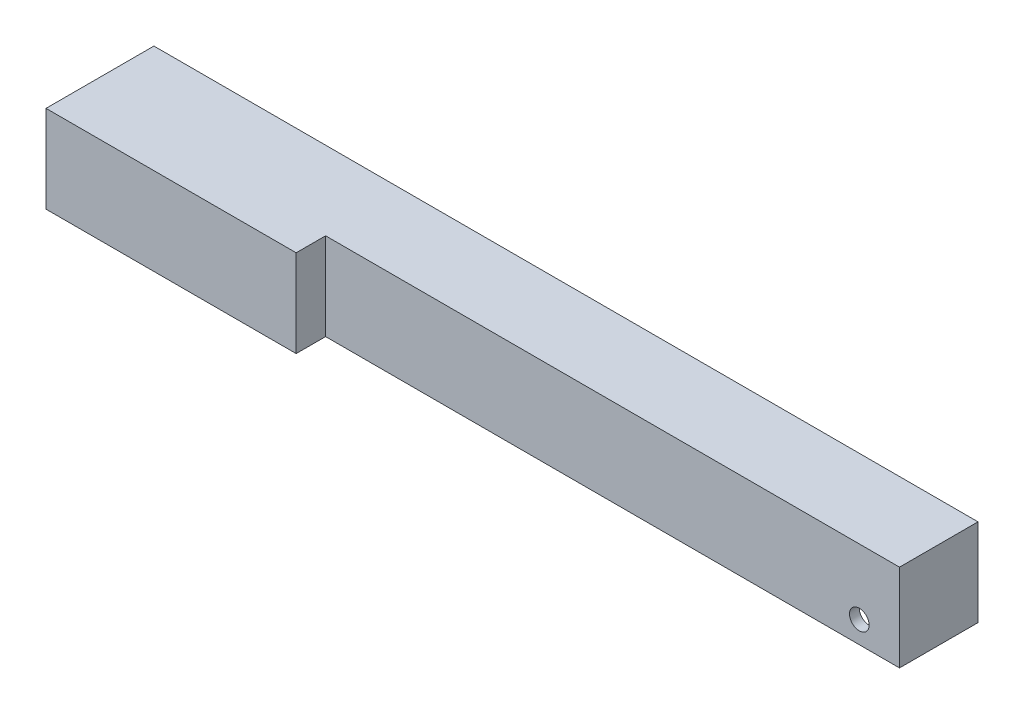
SolidWorks part; units mm, degrees
ref_plane "Front Plane" through (0, 0, 0) normal (0, 0, 1) x (1, 0, 0)
ref_plane "Top Plane" through (0, 0, 0) normal (0, 1, 0) x (1, 0, 0)
ref_plane "Right Plane" through (0, 0, 0) normal (1, 0, 0) x (0, 0, -1)
sketch "Sketch1" plane through (0, 0, 0) normal (0, 1, 0) x (1, 0, 0)
  line L1 (-84, -11) -> (84, -11)
  line L2 (-84, -11) -> (-84, 11)
  line L3 (-84, 11) -> (84, 11)
  line L4 (84, -11) -> (84, 11)
  line L5 (-84, -11) -> (84, 11) construction
  line L6 (-84, 11) -> (84, -11) construction
  point P0 (0, 0)
  dimension "D1" = 22
  dimension "D2" = 168
extrude "Boss-Extrude1" add sketch "Sketch1" against normal blind 17.8 contours L2 L3 L4 L1
sketch "Sketch8" plane through (0, 0, 11) normal (0, 0, 1) x (1, 0, 0)
  line L0 (84, 0) -> (51.2, -17.8) construction
  line L1 (-84, -17.8) -> (84, -17.8) construction
  line L3 (67.6, -8.9) -> (84, -8.9) construction
  line L4 (84, -17.8) -> (84, 0) construction
  line L5 (75.8, -8.9) -> (75.8, -17.8) construction
  circle A0 centre (75.8, -13.35) radius 2
  dimension "D1" = 4
extrude "Cut-Extrude4" cut sketch "Sketch8" against normal up to surface (22 mm away) up to face at (0, -8.9, -11)
sketch "Sketch5" plane through (0, 0, 0) normal (0, 1, 0) x (1, 0, 0)
  line L0 (-84, -11) -> (84, -11) construction
  line L1 (-33, -5) -> (84, -5)
  line L2 (-33, -5) -> (-33, -11)
  line L3 (-33, -11) -> (84, -11)
  line L4 (84, -5) -> (84, -11)
  line L5 (-33, -5) -> (84, -11) construction
  line L6 (-33, -11) -> (84, -5) construction
  line L7 (84, -11) -> (84, 11) construction
  point P0 (25.5, -8)
  dimension "D1" = 117
  dimension "D2" = 6
extrude "Cut-Extrude2" cut sketch "Sketch5" against normal up to surface (17.8 mm away) up to face at (0, -17.8, 0)
sketch "Sketch6" plane through (0, -17.8, 0) normal (0, -1, 0) x (1, 0, 0)
  line L0 (-82, 9) -> (-82, -9)
  line L1 (-82, -9) -> (82, -9)
  line L5 (-35, 9) -> (-82, 9)
  line L6 (-84, 11) -> (-33, 11) construction
  line L7 (-84, 11) -> (-84, -11) construction
  line L8 (-84, -11) -> (84, -11) construction
  line L13 (82, -9) -> (82, 3)
  line L14 (82, 3) -> (-35, 3)
  line L15 (-35, 3) -> (-35, 9)
  line L16 (84, 5) -> (84, -11) construction
  line L17 (-33, 5) -> (84, 5) construction
  line L18 (-33, 11) -> (-33, 5) construction
  dimension "D1" = 2
  dimension "D2" = 2
  dimension "D3" = 2
  dimension "D4" = 2
  dimension "D5" = 2
  dimension "D6" = 2
extrude "Cut-Extrude3" cut sketch "Sketch6" against normal offset from surface (15.8 mm away) 2 up to face at (-11, 0, 1.6667)
sketch "Sketch9" plane through (0, 0, 9) normal (0, 0, -1) x (-1, 0, 0)
  line L0 (82, -2) -> (82, -17.8) construction
  line L1 (35, -12.3) -> (82, -12.3)
  line L2 (35, -12.3) -> (35, -14.3)
  line L3 (35, -14.3) -> (82, -14.3)
  line L4 (82, -12.3) -> (82, -14.3)
  line L5 (35, -12.3) -> (82, -14.3) construction
  line L6 (35, -14.3) -> (82, -12.3) construction
  line L7 (35, -2) -> (35, -17.8) construction
  line L10 (35, -17.8) -> (82, -17.8) construction
  point P0 (58.5, -13.3)
  dimension "D1" = 2
  dimension "D2" = 3.5
extrude "Boss-Extrude2" add sketch "Sketch9" along normal up to surface (18 mm away) up to face at (0, -9.9, -9)
